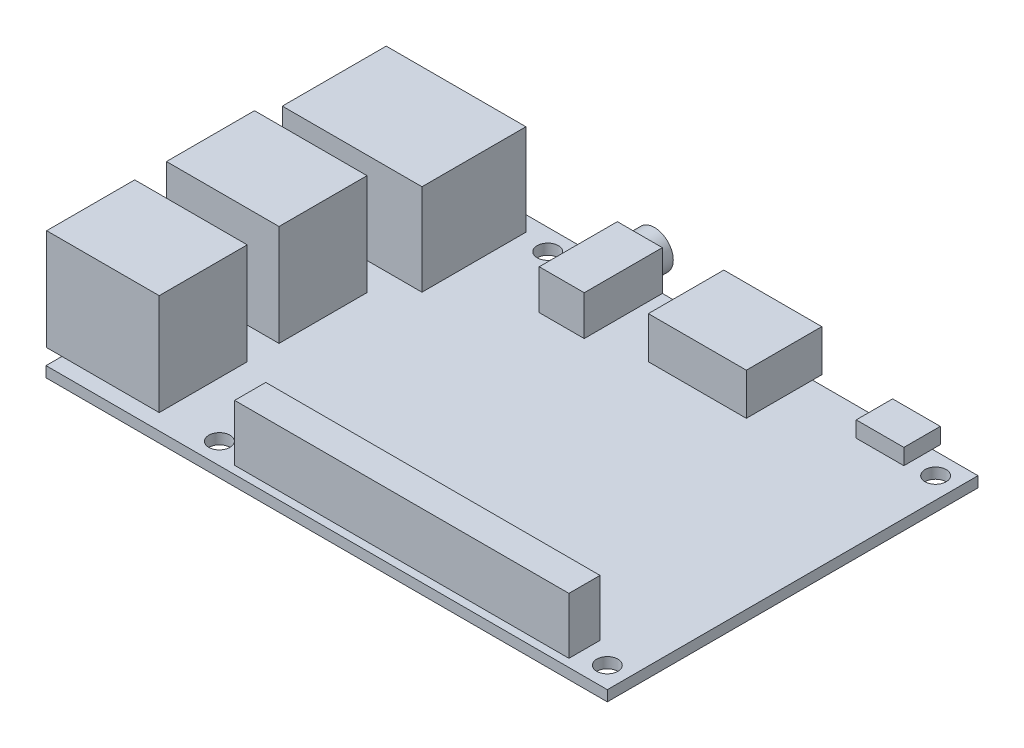
SolidWorks part; units mm, degrees
ref_plane "Front Plane" through (0, 0, 0) normal (0, 0, 1) x (1, 0, 0)
ref_plane "Top Plane" through (0, 0, 0) normal (0, 1, 0) x (1, 0, 0)
ref_plane "Right Plane" through (0, 0, 0) normal (1, 0, 0) x (0, 0, -1)
sketch "Sketch1" plane through (0, 0, 0) normal (0, 1, 0) x (1, 0, 0)
  line L1 (0, 0) -> (84.8, 0)
  line L2 (0, 0) -> (0, 56)
  line L3 (0, 56) -> (84.8, 56)
  line L4 (84.8, 0) -> (84.8, 56)
  dimension "D1" = 84.8
  dimension "D2" = 56
extrude "Boss-Extrude1" add sketch "Sketch1" along normal blind 1.6
hole_wizard "M3 Clearance Slot1" positions "Sketch4" profile "Sketch3" size "M3" standard "ANSI Metric" slot yes end condition through all
sketch "Sketch4" plane through (0, 1.6, 0) normal (0, 1, 0) x (1, 0, 0)
  line L0 (0, 0) -> (84.8, 0) construction
  line L1 (84.8, 0) -> (84.8, 56) construction
  line L2 (84.8, 56) -> (0, 56) construction
  line L3 (0, 56) -> (0, 0) construction
  point P0 (81.6, 3.2)
  point P2 (81.6, 52.8)
  point P4 (23, 52.8)
  point P6 (23, 3.2)
  dimension "D1" = 3.2
  dimension "D2" = 3.2
  dimension "D3" = 3.2
  dimension "D4" = 3.2
  dimension "D5" = 3.2
  dimension "D6" = 3.2
  dimension "D7" = 23
  dimension "D8" = 23
sketch "Sketch3" plane through (81.6, 1.6, -3.2) normal (1, 0, 0) x (0, 0, 1)
  line L0 (0, 0) -> (0, 1.6)
  line L1 (0, 1.6) -> (1.6, 1.6)
  line L2 (1.6, 1.6) -> (1.6, 0)
  line L5 (1.6, 0) -> (0, 0)
  line L11 (0, -6.35) -> (0, 107.95) construction
  dimension "Thru Hole Dia." = 3.2
  dimension "Thru Hole Depth" = 1.6
sketch "Sketch5" plane through (0, 1.6, 0) normal (0, 1, 0) x (1, 0, 0)
  line L0 (84.8, 0) -> (84.8, 56) construction
  line L1 (77.8, 1.2) -> (27.3, 1.2)
  line L2 (77.8, 1.2) -> (77.8, 5.9)
  line L3 (77.8, 5.9) -> (27.3, 5.9)
  line L4 (27.3, 1.2) -> (27.3, 5.9)
  line L5 (0, 0) -> (84.8, 0) construction
  dimension "D1" = 4.7
  dimension "D2" = 50.5
  dimension "D3" = 7
  dimension "D4" = 1.2
extrude "Boss-Extrude2" add sketch "Sketch5" along normal blind 8.5
sketch "Sketch6" plane through (0, 1.6, 0) normal (0, 1, 0) x (1, 0, 0)
  line L0 (0, 56) -> (0, 0) construction
  line L1 (-2.3, 53.7) -> (18.8, 53.7)
  line L2 (-2.3, 53.7) -> (-2.3, 38)
  line L3 (-2.3, 38) -> (18.8, 38)
  line L4 (18.8, 53.7) -> (18.8, 38)
  line L5 (84.8, 56) -> (0, 56) construction
  dimension "D1" = 15.7
  dimension "D2" = 21.1
  dimension "D3" = 18.8
  dimension "D4" = 2.3
extrude "Boss-Extrude3" add sketch "Sketch6" along normal blind 13.8
sketch "Sketch7" plane through (0, 1.6, 0) normal (0, 1, 0) x (1, 0, 0)
  line L1 (-2.3, 33.8) -> (14.7, 33.8)
  line L2 (-2.3, 33.8) -> (-2.3, 20.5)
  line L3 (-2.3, 20.5) -> (14.7, 20.5)
  line L4 (14.7, 33.8) -> (14.7, 20.5)
  line L5 (0, 38) -> (0, 0) construction
  line L6 (-2.3, 15.7) -> (14.7, 15.7)
  line L7 (-2.3, 15.7) -> (-2.3, 2.4)
  line L8 (-2.3, 2.4) -> (14.7, 2.4)
  line L9 (14.7, 15.7) -> (14.7, 2.4)
  line L10 (0, 0) -> (84.8, 0) construction
  line L11 (0, 38) -> (18.8, 38) construction
  dimension "D1" = 17
  dimension "D2" = 14.7
  dimension "D3" = 14.7
  dimension "D4" = 13.3
  dimension "D5" = 2.4
  dimension "D6" = 4.8
  dimension "D7" = 4.2
extrude "Boss-Extrude4" add sketch "Sketch7" along normal blind 15.3
sketch "Sketch8" plane through (0, 1.6, 0) normal (0, 1, 0) x (1, 0, 0)
  line L0 (84.8, 56) -> (0, 56) construction
  line L1 (70.7, 51.7) -> (77.9, 51.7)
  line L2 (70.7, 51.7) -> (70.7, 57.2)
  line L3 (70.7, 57.2) -> (77.9, 57.2)
  line L4 (77.9, 51.7) -> (77.9, 57.2)
  line L5 (84.8, 0) -> (84.8, 56) construction
  dimension "D1" = 7.2
  dimension "D2" = 5.5
  dimension "D3" = 1.2
  dimension "D4" = 6.9
extrude "Boss-Extrude5" add sketch "Sketch8" along normal blind 2.4
sketch "Sketch9" plane through (0, 1.6, 0) normal (0, 1, 0) x (1, 0, 0)
  line L0 (70.7, 56) -> (0, 56) construction
  line L1 (45, 46) -> (59.8, 46)
  line L2 (45, 46) -> (45, 57.4)
  line L3 (45, 57.4) -> (59.8, 57.4)
  line L4 (59.8, 46) -> (59.8, 57.4)
  line L5 (84.8, 0) -> (84.8, 56) construction
  dimension "D1" = 11.4
  dimension "D2" = 14.8
  dimension "D3" = 1.4
  dimension "D4" = 25
extrude "Boss-Extrude6" add sketch "Sketch9" along normal blind 6.3
sketch "Sketch10" plane through (0, 1.6, 0) normal (0, 1, 0) x (1, 0, 0)
  line L0 (45, 56) -> (0, 56) construction
  line L1 (30.3229, 44.19) -> (37.1229, 44.19)
  line L2 (30.3229, 44.19) -> (30.3229, 55.99)
  line L3 (30.3229, 55.99) -> (37.1229, 55.99)
  line L4 (37.1229, 44.19) -> (37.1229, 55.99)
  dimension "D1" = 6.8
  dimension "D2" = 11.8
  dimension "D3" = 0.01
extrude "Boss-Extrude7" add sketch "Sketch10" along normal blind 6
sketch "Sketch11" plane through (0, 0, -55.99) normal (0, 0, -1) x (-1, 0, 0)
  circle A0 centre (-33.7229, 4.6) radius 2.85
  dimension "D1" = 5.7
extrude "Boss-Extrude8" add sketch "Sketch11" along normal blind 2.2
